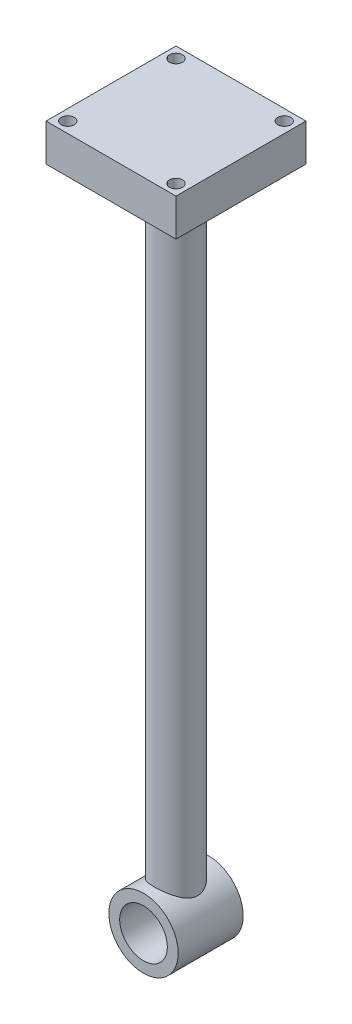
SolidWorks part; units mm, degrees
ref_plane "前视基准面" through (0, 0, 0) normal (0, 0, 1) x (1, 0, 0)
ref_plane "上视基准面" through (0, 0, 0) normal (0, 1, 0) x (1, 0, 0)
ref_plane "右视基准面" through (0, 0, 0) normal (1, 0, 0) x (0, 0, -1)
sketch "草图1" plane through (0, 0, 0) normal (0, 0, 1) x (1, 0, 0)
  circle A0 centre (0, 0) radius 5.5
  circle A1 centre (0, 0) radius 8
  dimension "D1" = 11
  dimension "D2" = 16
extrude "凸台-拉伸1" add sketch "草图1" along normal mid plane 15
ref_plane "基准面1" through (0, 150, 0) normal (0, 1, 0) x (1, 0, 0)
sketch "草图2" plane through (0, 150, 0) normal (0, 1, 0) x (1, 0, 0)
  circle A1 centre (0, 0) radius 5
  dimension "D1" = 10
extrude "凸台-拉伸2" add sketch "草图2" against normal up to surface (142 mm away)
sketch "草图3" plane through (0, 150, 0) normal (0, 1, 0) x (1, 0, 0)
  line L1 (-15, 15) -> (15, 15)
  line L2 (-15, 15) -> (-15, -15)
  line L3 (-15, -15) -> (15, -15)
  line L4 (15, 15) -> (15, -15)
  line L5 (0, -15) -> (0, 15) construction
  line L6 (-15, 0) -> (15, 0) construction
  point P0 (0, 0)
  dimension "D1" = 30
  dimension "D2" = 30
extrude "凸台-拉伸3" add sketch "草图3" along normal up to surface (8.611 mm away)
sketch "草图4" plane through (0, 158.611, 0) normal (0, 1, 0) x (1, 0, 0)
  line L1 (-12.5, 12.5) -> (12.5, 12.5) construction
  line L2 (-12.5, 12.5) -> (-12.5, -12.5) construction
  line L3 (-12.5, -12.5) -> (12.5, -12.5) construction
  line L4 (12.5, 12.5) -> (12.5, -12.5) construction
  line L5 (0, -12.5) -> (0, 12.5) construction
  line L6 (-12.5, 0) -> (12.5, 0) construction
  circle A0 centre (12.5, -12.5) radius 1.5
  circle A1 centre (12.5, 12.5) radius 1.5
  circle A2 centre (-12.5, -12.5) radius 1.5
  circle A3 centre (-12.5, 12.5) radius 1.5
  point P0 (0, 0)
  dimension "D3" = 3
  dimension "D1" = 25
  dimension "D2" = 25
extrude "切除-拉伸1" cut sketch "草图4" against normal blind 10
